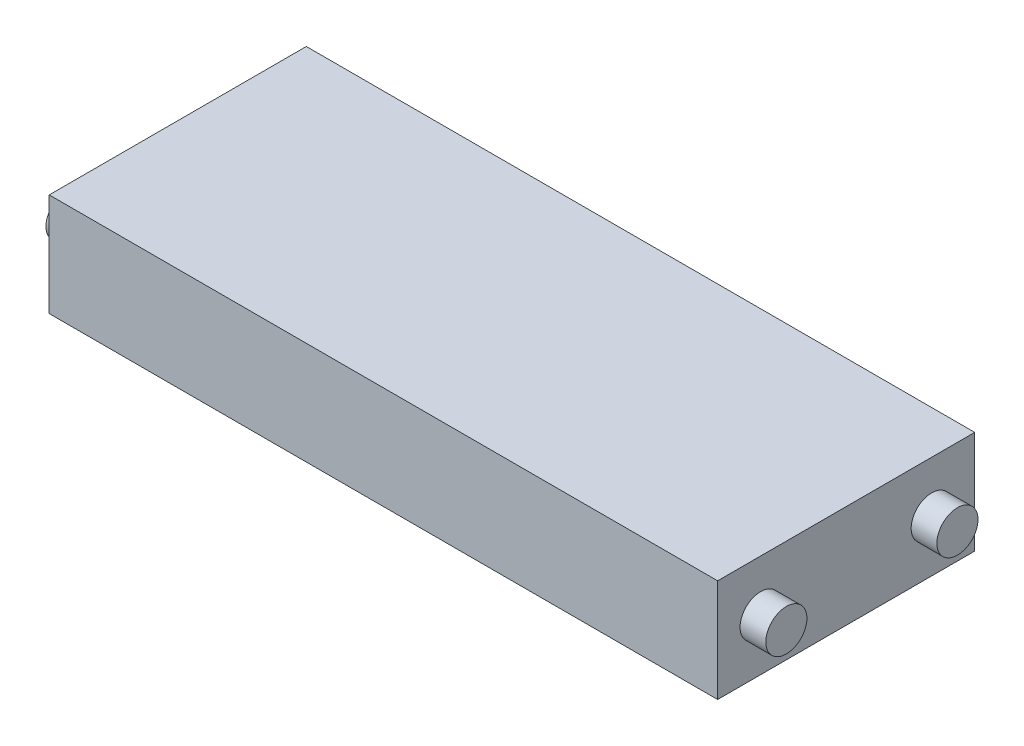
SolidWorks part; units mm, degrees
ref_plane "Front Plane" through (0, 0, 0) normal (0, 0, 1) x (1, 0, 0)
ref_plane "Top Plane" through (0, 0, 0) normal (0, 1, 0) x (1, 0, 0)
ref_plane "Right Plane" through (0, 0, 0) normal (1, 0, 0) x (0, 0, -1)
sketch "Sketch1" plane through (0, 0, 0) normal (0, 1, 0) x (1, 0, 0)
  line L1 (-32.5, 12.5) -> (32.5, 12.5)
  line L2 (-32.5, 12.5) -> (-32.5, -12.5)
  line L3 (-32.5, -12.5) -> (32.5, -12.5)
  line L4 (32.5, 12.5) -> (32.5, -12.5)
  point P4 (0, -12.5)
  point P8 (-32.5, 0)
  dimension "D1" = 65
  dimension "D2" = 25
extrude "Boss-Extrude1" add sketch "Sketch1" along normal blind 10
sketch "Sketch2" plane through (32.5, 0, 0) normal (1, 0, 0) x (0, 0, -1)
  line L0 (0, 0) -> (0, 3.5133) construction
  circle A0 centre (-8.3191, 5) radius 2
  circle A1 centre (8.3191, 5) radius 2
  point P4 (0, 0)
  dimension "D2" = 4
  dimension "D1" = 5
extrude "Boss-Extrude2" add sketch "Sketch2" along normal blind 2.5 and the other way offset from surface (67.5 mm away) 2.5 other way up to face at (-32.5, 5, 0)
